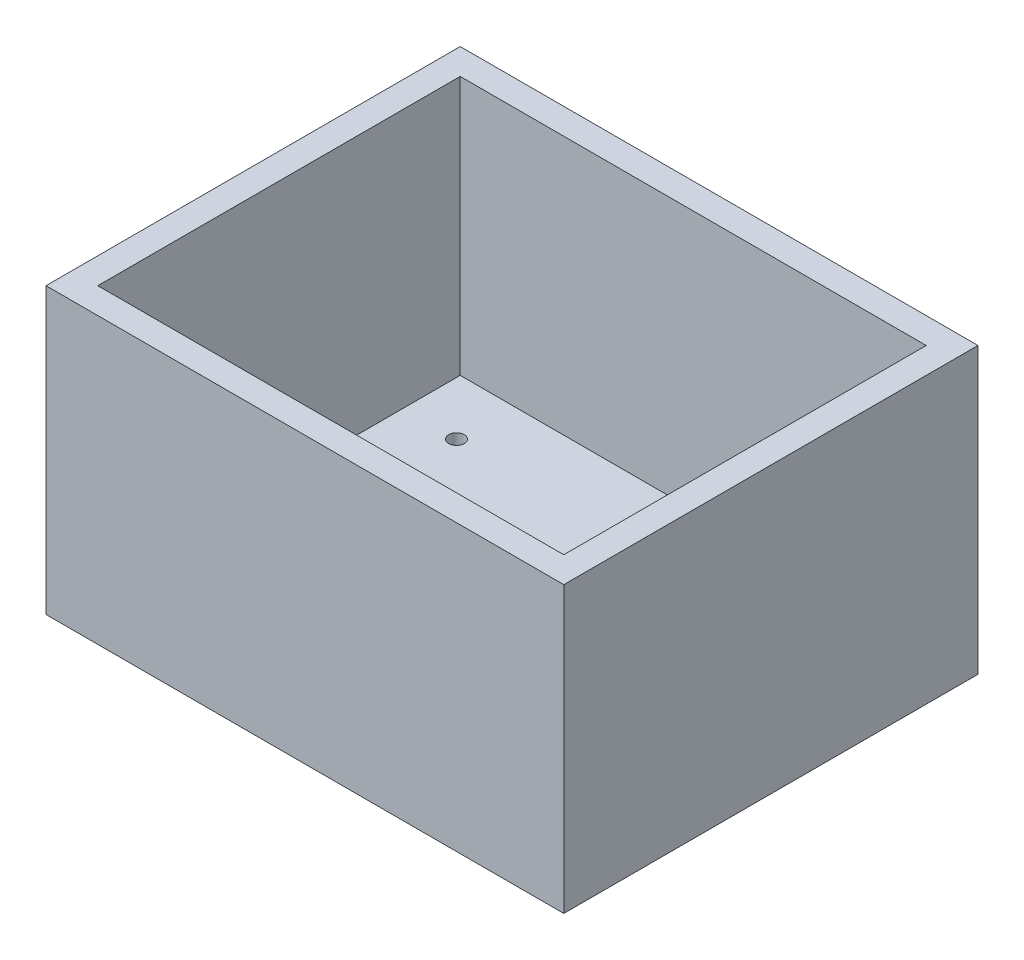
SolidWorks part; units mm, degrees
ref_plane "Front Plane" through (0, 0, 0) normal (0, 0, 1) x (1, 0, 0)
ref_plane "Top Plane" through (0, 0, 0) normal (0, 1, 0) x (1, 0, 0)
ref_plane "Right Plane" through (0, 0, 0) normal (1, 0, 0) x (0, 0, -1)
sketch "Sketch1" plane through (0, 0, 0) normal (0, 1, 0) x (1, 0, 0)
  line L1 (-50, 40) -> (50, 40)
  line L2 (-50, 40) -> (-50, -40)
  line L3 (-50, -40) -> (50, -40)
  line L4 (50, 40) -> (50, -40)
  line L5 (-50, 40) -> (50, -40) construction
  line L6 (-50, -40) -> (50, 40) construction
  point P0 (0, 0)
  dimension "D1" = 80
  dimension "D2" = 100
extrude "Boss-Extrude1" add sketch "Sketch1" along normal blind 55
sketch "Sketch3" plane through (0, 55, 0) normal (0, 1, 0) x (1, 0, 0)
  line L1 (-45, 35) -> (45, 35)
  line L2 (-45, 35) -> (-45, -35)
  line L3 (-45, -35) -> (45, -35)
  line L4 (45, 35) -> (45, -35)
  line L5 (-45, 35) -> (45, -35) construction
  line L6 (-45, -35) -> (45, 35) construction
  point P0 (0, 0)
  dimension "D1" = 90
  dimension "D2" = 70
extrude "Cut-Extrude1" cut sketch "Sketch3" against normal blind 50
sketch "Sketch5" plane through (0, 5, 0) normal (0, 1, 0) x (1, 0, 0)
  line L0 (0, 35) -> (0, -35) construction
  line L1 (45, 35) -> (-45, 35) construction
  line L2 (-45, -35) -> (45, -35) construction
  line L3 (-45, 0) -> (45, 0) construction
  line L4 (-45, 35) -> (-45, -35) construction
  line L5 (45, -35) -> (45, 35) construction
  circle A0 centre (-34.7015, 23.9833) radius 1.5
  circle A1 centre (34.7015, 23.9833) radius 1.5
  circle A2 centre (34.7015, -23.9833) radius 1.5
  circle A3 centre (-34.7015, -23.9833) radius 1.5
  dimension "D1" = 3
extrude "Cut-Extrude2" cut sketch "Sketch5" against normal blind 50
